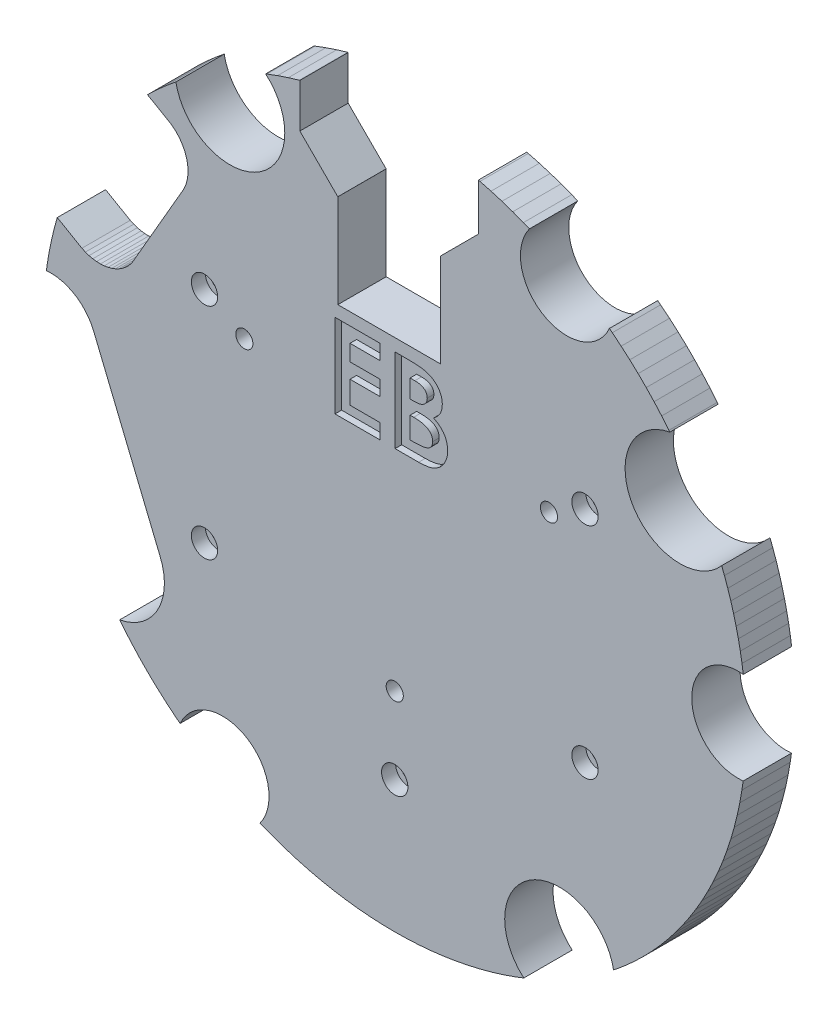
SolidWorks part; units mm, degrees
ref_plane "Płaszczyzna przednia" through (0, 0, 0) normal (0, 0, 1) x (1, 0, 0)
ref_plane "Płaszczyzna górna" through (0, 0, 0) normal (0, 1, 0) x (1, 0, 0)
ref_plane "Płaszczyzna prawa" through (0, 0, 0) normal (1, 0, 0) x (0, 0, -1)
sketch "mandaryna baza " plane through (0, 0, 0) normal (0, 0, 1) x (1, 0, 0)
  line L0 (16.9072, 3.25) -> (54.9039, 3.25)
  line L1 (30.2665, 45.9232) -> (11.2682, 13.017)
  line L2 (5.639, 16.267) -> (24.6374, 49.1732)
  line L3 (-24.6374, 49.1732) -> (-5.639, 16.267)
  line L4 (-11.2682, 13.017) -> (-30.2665, 45.9232)
  line L5 (-54.9039, 3.25) -> (-16.9072, 3.25)
  line L6 (4.5506, 66.6591) -> (4.5491, 66.657) construction
  line L7 (24.4667, 51.9252) -> (4.5506, 66.6591) construction
  line L8 (5.8555, 16.142) -> (24.861, 49.0605) construction
  line L9 (-24.861, 49.0605) -> (-5.8555, 16.142) construction
  line L10 (-4.5491, 66.657) -> (-4.5506, 66.6591) construction
  line L11 (30.0571, 46.0605) -> (11.0517, 13.142) construction
  line L12 (67.2135, 4.9608) -> (71.9198, 8.4424) construction
  line L13 (16.9072, 3) -> (54.9181, 3) construction
  line L14 (-16.9072, -3.25) -> (-54.9039, -3.25)
  line L15 (-30.2665, -45.9232) -> (-11.2682, -13.017)
  line L16 (54.9181, -3) -> (16.9072, -3) construction
  line L17 (71.9198, -8.4424) -> (67.2135, -4.9608) construction
  line L18 (11.0517, -13.142) -> (30.0571, -46.0605) construction
  line L19 (-5.639, -16.267) -> (-24.6374, -49.1732)
  line L20 (24.6374, -49.1732) -> (5.639, -16.267)
  line L21 (11.2682, -13.017) -> (30.2665, -45.9232)
  line L22 (54.9039, -3.25) -> (16.9072, -3.25)
  line L23 (4.5506, -66.6591) -> (24.4667, -51.9252) construction
  line L24 (4.5491, -66.657) -> (4.5506, -66.6591) construction
  line L25 (-4.5506, -66.6591) -> (-4.5491, -66.657) construction
  line L26 (-24.4667, -51.9252) -> (-4.5506, -66.6591) construction
  line L27 (-67.2135, -4.9608) -> (-71.9198, -8.4424) construction
  line L28 (-16.9072, -3) -> (-54.9181, -3) construction
  line L29 (-54.9181, 3) -> (-16.9072, 3) construction
  line L30 (-71.9198, 8.4424) -> (-67.2135, 4.9608) construction
  line L31 (-11.0517, 13.142) -> (-30.0571, 46.0605) construction
  line L37 (-13.1504, 53.4048) -> (-13.1504, 36.9511)
  line L38 (-13.1504, 36.9511) -> (10.6176, 36.9511)
  line L39 (10.6176, 36.9511) -> (10.6176, 53.9654)
  circle A0 centre (0, 0) radius 85 construction
  circle A1 centre (0, 0) radius 6 construction
  arc A2 (11.2682, 13.017) -> (16.9072, 3.25) centre (16.9072, 9.7614) ccw
  arc A3 (-5.639, 16.267) -> (5.639, 16.267) centre (0, 19.5227) ccw
  arc A4 (-16.9072, 3.25) -> (-11.2682, 13.017) centre (-16.9072, 9.7614) ccw
  arc A5 (25.0093, 49.3174) -> (24.4667, 51.9252) centre (23.2772, 50.3174) ccw construction
  arc A6 (-5.8555, 16.142) -> (5.8555, 16.142) centre (0, 19.5227) ccw construction
  arc A7 (-4.5491, 66.657) -> (-0.4915, 64.6309) centre (-0.5295, 69.6307) ccw construction
  arc A8 (0.4915, 64.6309) -> (-0.4915, 64.6309) centre (0, 0) ccw construction
  arc A9 (0.4915, 64.6309) -> (4.5491, 66.657) centre (0.5295, 69.6307) ccw construction
  arc A10 (51.1946, 58.8482) -> (35.971, 56.3035) centre (44.6312, 51.3035) ccw construction
  arc A11 (75.6742, 18.9054) -> (51.1946, 58.8482) centre (0, 0) ccw construction
  arc A12 (71.9198, 8.4424) -> (75.6742, 18.9054) centre (65.9724, 16.4816) ccw construction
  arc A13 (61.2662, 3) -> (67.2135, 4.9608) centre (61.2662, 13) ccw construction
  arc A14 (11.0517, 13.142) -> (16.9072, 3) centre (16.9072, 9.7614) ccw construction
  arc A15 (-11.2682, -13.017) -> (-16.9072, -3.25) centre (-16.9072, -9.7614) ccw
  arc A16 (67.2135, -4.9608) -> (61.2662, -3) centre (61.2662, -13) ccw construction
  arc A17 (75.6742, -18.9054) -> (71.9198, -8.4424) centre (65.9724, -16.4816) ccw construction
  arc A18 (14.9118, -76.5613) -> (56.0831, -54.2097) centre (0, 0) ccw construction
  arc A19 (3, -66.7458) -> (14.9118, -76.5613) centre (13, -66.7458) ccw construction
  arc A20 (16.9072, -3) -> (11.0517, -13.142) centre (16.9072, -9.7614) ccw construction
  arc A21 (5.639, -16.267) -> (-5.639, -16.267) centre (0, -19.5227) ccw
  arc A22 (4.5491, -66.657) -> (0.4915, -64.6309) centre (0.5295, -69.6307) ccw construction
  arc A23 (-0.4915, -64.6309) -> (0.4915, -64.6309) centre (0, 0) ccw construction
  arc A24 (-0.4915, -64.6309) -> (-4.5491, -66.657) centre (-0.5295, -69.6307) ccw construction
  arc A25 (-25.0093, -49.3174) -> (-24.4667, -51.9252) centre (-23.2772, -50.3174) ccw construction
  arc A26 (5.8555, -16.142) -> (-5.8555, -16.142) centre (0, -19.5227) ccw construction
  arc A27 (16.9072, -3.25) -> (11.2682, -13.017) centre (16.9072, -9.7614) ccw
  arc A28 (30.2665, -45.9232) -> (54.9039, -3.25) centre (0, 0) ccw
  arc A29 (24.6374, 49.1732) -> (10.6176, 53.9654) centre (0, 0) ccw
  arc A30 (-51.1946, -58.8482) -> (-35.971, -56.3035) centre (-44.6312, -51.3035) ccw construction
  arc A31 (-75.6742, -18.9054) -> (-51.1946, -58.8482) centre (0, 0) ccw construction
  arc A32 (-71.9198, -8.4424) -> (-75.6742, -18.9054) centre (-65.9724, -16.4816) ccw construction
  arc A33 (-61.2662, -3) -> (-67.2135, -4.9608) centre (-61.2662, -13) ccw construction
  arc A34 (-11.0517, -13.142) -> (-16.9072, -3) centre (-16.9072, -9.7614) ccw construction
  arc A35 (-30.2665, 45.9232) -> (-54.9039, 3.25) centre (0, 0) ccw
  arc A36 (-54.9039, -3.25) -> (-30.2665, -45.9232) centre (0, 0) ccw
  arc A37 (-24.6374, -49.1732) -> (24.6374, -49.1732) centre (0, 0) ccw
  arc A38 (54.9039, 3.25) -> (30.2665, 45.9232) centre (0, 0) ccw
  arc A39 (-67.2135, 4.9608) -> (-61.2662, 3) centre (-61.2662, 13) ccw construction
  arc A40 (-75.6742, 18.9054) -> (-71.9198, 8.4424) centre (-65.9724, 16.4816) ccw construction
  arc A41 (-51.1946, 58.8482) -> (-75.6742, 18.9054) centre (0, 0) ccw construction
  arc A42 (-35.971, 56.3035) -> (-51.1946, 58.8482) centre (-44.6312, 51.3035) ccw construction
  arc A43 (-16.9072, 3) -> (-11.0517, 13.142) centre (-16.9072, 9.7614) ccw construction
  arc A44 (-13.1504, 53.4048) -> (-24.6374, 49.1732) centre (0, 0) ccw
extrude "Dodanie-wyciągnięcie1" add sketch "mandaryna baza " along normal blind 5
sketch "MB_wyciecia" plane through (0, 0, 0) normal (0, 0, 1) x (1, 0, 0)
  line L0 (-0.1242, -22.5327) -> (-0.3125, 0) construction
  line L1 (-34.4185, 20.0049) -> (-0.3125, 0) construction
  line L2 (13.0498, 7.7147) -> (34.7962, 20.27) construction
  line L7 (-35.0924, 72.0577) -> (-32.5738, 67.4522)
  line L8 (-42.3633, 62.4733) -> (-44.721, 66.557)
  line L9 (19.0018, 77.646) -> (19.0018, 67.2099)
  line L10 (19.0018, 67.2099) -> (10.3758, 58.5839)
  line L11 (10.3758, 58.5839) -> (10.3758, 37.3074)
  line L12 (10.3758, 37.3074) -> (-12.9922, 37.3074)
  line L13 (-12.9922, 37.3074) -> (-12.9922, 58.5739)
  line L14 (-12.9922, 58.5739) -> (-21.6382, 67.2099)
  line L15 (-21.6382, 67.2099) -> (-21.7619, 77.0835)
  line L19 (42.2923, -62.1866) -> (44.5033, -66.2834)
  line L20 (-58.3058, 54.9924) -> (-50.9165, 49.4506)
  line L21 (-70.2019, 38.6255) -> (-62.5311, 33.1574)
  line L23 (-74.5615, -9.724) -> (-68.7602, -8.3848)
  line L24 (-76.1011, -24.6775) -> (-65.5639, -22.245)
  line L25 (67.774, 32.961) -> (71.6123, 35.0537)
  line L26 (62.1773, 42.4277) -> (65.9654, 44.8239)
  line L28 (32.3345, -66.7767) -> (34.11, -72.1952)
  line L29 (-62.2802, -42.12) -> (-66.1005, -44.9806)
  line L30 (-67.4562, -32.4335) -> (-72.2043, -34.4007)
  line L31 (-58.3058, 54.9924) -> (-58.3719, 55.055)
  line L32 (-70.2019, 38.6255) -> (-70.3266, 38.7295)
  line L34 (-76.1011, -24.6775) -> (-76.3992, -24.7542)
  line L35 (-72.2043, -34.4007) -> (-72.5196, -34.4687)
  line L36 (-66.1005, -44.9806) -> (-66.3559, -45.1687)
  line L37 (34.11, -72.1952) -> (34.1253, -72.2217)
  arc A1 (-42.3633, 62.4733) -> (-32.5738, 67.4522) centre (-37.5482, 65.1194) ccw
  arc A3 (-62.5311, 33.1574) -> (-50.9165, 49.4506) centre (-56.5654, 41.1911) ccw
  arc A4 (-65.5639, -22.245) -> (-68.7602, -8.3848) centre (-67.0693, -15.2935) ccw
  arc A5 (-62.2802, -42.12) -> (-67.4562, -32.4335) centre (-64.9966, -37.3454) ccw
  arc A7 (62.1773, 42.4277) -> (67.774, 32.961) centre (64.9255, 37.6647) ccw
  arc A8 (42.2923, -62.1866) -> (32.3345, -66.7767) centre (37.4627, -64.8056) ccw
  arc A9 (-21.7619, 77.0835) -> (-35.0924, 72.0577) centre (-0.3125, 0) ccw
  arc A10 (-44.721, 66.557) -> (-58.3719, 55.055) centre (-0.3125, 0) ccw
  arc A11 (-70.3266, 38.7295) -> (-79.6124, 10.6528) centre (-0.3125, 0) ccw
  arc A12 (-76.3992, -24.7542) -> (-72.5196, -34.4687) centre (-0.3125, 0) ccw
  arc A13 (-66.3559, -45.1687) -> (-48.9339, -63.5445) centre (-0.3125, 0) ccw
  arc A14 (44.5033, -66.2834) -> (78.9866, -10.6577) centre (-0.3125, 0) ccw
  arc A15 (65.9654, 44.8239) -> (48.7749, 63.1852) centre (-0.3125, 0) ccw
  arc A16 (79.0174, 10.4265) -> (78.9866, -10.6577) centre (78.1738, -0.1144) ccw
  arc A18 (-30.7368, -74.0021) -> (-48.9339, -63.5445) centre (-39.186, -67.6433) ccw
  arc A21 (30.5908, 73.8033) -> (48.7749, 63.1852) centre (39.186, 67.6433) ccw
  circle A22 centre (38.9878, -67.7577) radius 10.5746
  circle A23 centre (-38.9878, 67.7577) radius 10.5746
  arc A24 (30.5908, 73.8033) -> (19.0018, 77.646) centre (-0.3125, 0) ccw
  arc A25 (79.0174, 10.4265) -> (71.6123, 35.0537) centre (-0.3125, 0) ccw
  arc A26 (-30.7368, -74.0021) -> (34.1253, -72.2217) centre (-0.3125, 0) ccw
  arc A28 (-74.5615, -9.724) -> (-79.6124, 10.6528) centre (-78.3301, 0.1563) ccw
  arc A29 (-84.5664, -8.3092) -> (-82.6226, -9.4789) centre (-78.1738, 0.1144) ccw
  point P46 (0, 0)
  dimension "D6" = 10.9879
  dimension "D7" = 10.9884
  dimension "D8" = 20.013
  dimension "D9" = 14.2253
  dimension "D10" = 10.9979
  dimension "D11" = 160.0243
  dimension "D3" = 80.0122
  dimension "D2" = 39.54
  dimension "D4" = 6
  dimension "D13" = 40.54
  dimension "D15" = 39.54
sketch "EB_" plane through (0, 0, 0) normal (0, 0, 1) x (1, 0, 0)
  line L0 (0, 0) -> (-22.7294, 43.3106) construction
  line L1 (0, 0) -> (25.5306, 43.3106) construction
  line L2 (0, 0) -> (-19.5544, -22.7294)
  line L3 (0, 0) -> (22.3556, -22.7294)
  line L4 (-71.5796, -7.9834) -> (-71.3126, -9.14)
  line L5 (-71.3126, -9.14) -> (-68.5352, -8.4988)
  line L660 (-59.4357, 22.62) -> (-59.654, 22.2418)
  line L661 (-59.654, 22.2418) -> (-60.1628, 21.5318)
  line L662 (-60.1628, 21.5318) -> (-60.7387, 20.8751)
  line L663 (-60.7387, 20.8751) -> (-61.3762, 20.278)
  line L664 (-61.3762, 20.278) -> (-62.0692, 19.7462)
  line L665 (-62.0692, 19.7462) -> (-62.811, 19.285)
  line L666 (-62.811, 19.285) -> (-63.5944, 18.8986)
  line L667 (-63.5944, 18.8986) -> (-64.4119, 18.591)
  line L668 (-64.4119, 18.591) -> (-65.2556, 18.3649)
  line L669 (-65.2556, 18.3649) -> (-66.1174, 18.2226)
  line L670 (-66.1174, 18.2226) -> (-66.989, 18.1655)
  line L671 (-66.989, 18.1655) -> (-67.862, 18.1941)
  line L672 (-67.862, 18.1941) -> (-68.728, 18.3081)
  line L673 (-68.728, 18.3081) -> (-69.5787, 18.5064)
  line L674 (-69.5787, 18.5064) -> (-70.4058, 18.7872)
  line L675 (-70.4058, 18.7872) -> (-71.2014, 19.1477)
  line L676 (-71.2014, 19.1477) -> (-71.5796, 19.366)
  line L677 (-71.5796, 19.366) -> (-76.8174, 22.3901)
  line L678 (-76.8174, 22.3901) -> (-76.8834, 22.1744)
  line L679 (-76.8834, 22.1744) -> (-77.5625, 19.6678)
  line L680 (-77.5625, 19.6678) -> (-78.1599, 17.1405)
  line L681 (-78.1599, 17.1405) -> (-78.6749, 14.5952)
  line L682 (-78.6749, 14.5952) -> (-79.1071, 12.0345)
  line L683 (-79.1071, 12.0345) -> (-79.2897, 10.6872)
  line L693 (-68.5352, -8.4988) -> (-68.1939, -8.42)
  line L694 (-68.1939, -8.42) -> (-67.4966, -8.3528)
  line L695 (-67.4966, -8.3528) -> (-66.7965, -8.3773)
  line L696 (-66.7965, -8.3773) -> (-66.1056, -8.4929)
  line L697 (-66.1056, -8.4929) -> (-65.4357, -8.6977)
  line L698 (-65.4357, -8.6977) -> (-64.7982, -8.9882)
  line L699 (-64.7982, -8.9882) -> (-64.2042, -9.3594)
  line L700 (-64.2042, -9.3594) -> (-63.6636, -9.805)
  line L701 (-63.6636, -9.805) -> (-63.1859, -10.3174)
  line L702 (-63.1859, -10.3174) -> (-62.7791, -10.8877)
  line L703 (-62.7791, -10.8877) -> (-62.4502, -11.5062)
  line L704 (-62.4502, -11.5062) -> (-62.2049, -12.1624)
  line L705 (-62.2049, -12.1624) -> (-62.1261, -12.5037)
  line L706 (-62.1261, -12.5037) -> (-61.3306, -15.949)
  line L707 (-61.3306, -15.949) -> (-61.2518, -16.2903)
  line L708 (-61.2518, -16.2903) -> (-61.1847, -16.9876)
  line L709 (-61.1847, -16.9876) -> (-61.2092, -17.6877)
  line L710 (-61.2092, -17.6877) -> (-61.3248, -18.3787)
  line L711 (-61.3248, -18.3787) -> (-61.5296, -19.0486)
  line L712 (-61.5296, -19.0486) -> (-61.8201, -19.686)
  line L713 (-61.8201, -19.686) -> (-62.1913, -20.2801)
  line L714 (-62.1913, -20.2801) -> (-62.6369, -20.8206)
  line L715 (-62.6369, -20.8206) -> (-63.1492, -21.2984)
  line L716 (-63.1492, -21.2984) -> (-63.7196, -21.7052)
  line L717 (-63.7196, -21.7052) -> (-64.3381, -22.0341)
  line L718 (-64.3381, -22.0341) -> (-64.9942, -22.2794)
  line L719 (-64.9942, -22.2794) -> (-65.3355, -22.3582)
  line L720 (-65.3355, -22.3582) -> (-76.0559, -24.8332)
  line L721 (-76.0559, -24.8332) -> (-75.5463, -26.3728)
  line L722 (-75.5463, -26.3728) -> (-74.6507, -28.8104)
  line L723 (-74.6507, -28.8104) -> (-74.4178, -29.3858)
  line L756 (-62.6093, -49.8114) -> (-61.8317, -50.7929)
  line L757 (-61.8317, -50.7929) -> (-60, -52.944)
  line L758 (-60, -52.944) -> (-58.0936, -55.0292)
  line L759 (-58.0936, -55.0292) -> (-56.1147, -57.0457)
  line L760 (-56.1147, -57.0457) -> (-54.0659, -58.9911)
  line L761 (-54.0659, -58.9911) -> (-51.9496, -60.863)
  line L762 (-51.9496, -60.863) -> (-49.7687, -62.659)
  line L763 (-49.7687, -62.659) -> (-48.854, -63.3595)
  line L770 (-30.6643, -73.9045) -> (-30.3309, -74.048)
  line L771 (-30.3309, -74.048) -> (-27.6979, -75.0726)
  line L772 (-27.6979, -75.0726) -> (-25.0304, -76.0036)
  line L773 (-25.0304, -76.0036) -> (-22.3317, -76.8399)
  line L774 (-22.3317, -76.8399) -> (-19.6051, -77.5804)
  line L775 (-19.6051, -77.5804) -> (-16.8541, -78.2241)
  line L776 (-16.8541, -78.2241) -> (-14.0821, -78.7703)
  line L777 (-14.0821, -78.7703) -> (-11.2926, -79.2184)
  line L778 (-11.2926, -79.2184) -> (-8.4889, -79.5676)
  line L779 (-8.4889, -79.5676) -> (-5.6747, -79.8177)
  line L780 (-5.6747, -79.8177) -> (-2.8534, -79.9683)
  line L781 (-2.8534, -79.9683) -> (-0.0286, -80.0192)
  line L782 (-0.0286, -80.0192) -> (2.7963, -79.9703)
  line L783 (2.7963, -79.9703) -> (5.6177, -79.8218)
  line L784 (5.6177, -79.8218) -> (8.4321, -79.5737)
  line L785 (8.4321, -79.5737) -> (11.236, -79.2264)
  line L786 (11.236, -79.2264) -> (14.0259, -78.7804)
  line L787 (14.0259, -78.7804) -> (16.7983, -78.2361)
  line L788 (16.7983, -78.2361) -> (19.5497, -77.5943)
  line L789 (19.5497, -77.5943) -> (22.2768, -76.8558)
  line L790 (22.2768, -76.8558) -> (24.9761, -76.0215)
  line L791 (24.9761, -76.0215) -> (27.6443, -75.0924)
  line L792 (27.6443, -75.0924) -> (29.3845, -74.4166)
  line L825 (49.8125, -62.6148) -> (50.2037, -62.3107)
  line L826 (50.2037, -62.3107) -> (52.3536, -60.5156)
  line L827 (52.3536, -60.5156) -> (54.4394, -58.6463)
  line L828 (54.4394, -58.6463) -> (56.4584, -56.7052)
  line L829 (56.4584, -56.7052) -> (58.4083, -54.6947)
  line L830 (58.4083, -54.6947) -> (60.2867, -52.6171)
  line L831 (60.2867, -52.6171) -> (62.0911, -50.475)
  line L832 (62.0911, -50.475) -> (63.8195, -48.2711)
  line L833 (63.8195, -48.2711) -> (65.4698, -46.0081)
  line L834 (65.4698, -46.0081) -> (67.0398, -43.6887)
  line L835 (67.0398, -43.6887) -> (68.5277, -41.3158)
  line L836 (68.5277, -41.3158) -> (69.9316, -38.8923)
  line L837 (69.9316, -38.8923) -> (71.2498, -36.4211)
  line L838 (71.2498, -36.4211) -> (72.4808, -33.9053)
  line L839 (72.4808, -33.9053) -> (73.623, -31.348)
  line L840 (73.623, -31.348) -> (74.6749, -28.7523)
  line L841 (74.6749, -28.7523) -> (75.6354, -26.1213)
  line L842 (75.6354, -26.1213) -> (76.5032, -23.4583)
  line L843 (76.5032, -23.4583) -> (77.2773, -20.7666)
  line L844 (77.2773, -20.7666) -> (77.9567, -18.0495)
  line L845 (77.9567, -18.0495) -> (78.5407, -15.3102)
  line L846 (78.5407, -15.3102) -> (79.0284, -12.5522)
  line L847 (79.0284, -12.5522) -> (79.2994, -10.6289)
  line L856 (79.3336, 10.3964) -> (79.0449, 12.4201)
  line L857 (79.0449, 12.4201) -> (78.6613, 14.6547)
  line L858 (78.6613, 14.6547) -> (78.2145, 16.8775)
  line L859 (78.2145, 16.8775) -> (77.7049, 19.0868)
  line L860 (77.7049, 19.0868) -> (77.1329, 21.2808)
  line L861 (77.1329, 21.2808) -> (76.499, 23.4576)
  line L862 (76.499, 23.4576) -> (75.8037, 25.6157)
  line L863 (75.8037, 25.6157) -> (75.0475, 27.7531)
  line L864 (75.0475, 27.7531) -> (74.4174, 29.3854)
  line L897 (62.6156, 49.8127) -> (62.4143, 50.0722)
  line L898 (62.4143, 50.0722) -> (60.7549, 52.0732)
  line L899 (60.7549, 52.0732) -> (59.0313, 54.0192)
  line L900 (59.0313, 54.0192) -> (57.2455, 55.9082)
  line L901 (57.2455, 55.9082) -> (55.3992, 57.7382)
  line L902 (55.3992, 57.7382) -> (53.4945, 59.5072)
  line L903 (53.4945, 59.5072) -> (51.5333, 61.2135)
  line L904 (51.5333, 61.2135) -> (49.5177, 62.8551)
  line L905 (49.5177, 62.8551) -> (48.8544, 63.3604)
  line L913 (30.6602, 73.899) -> (29.2981, 74.4606)
  line L914 (29.2981, 74.4606) -> (26.864, 75.373)
  line L915 (26.864, 75.373) -> (24.4015, 76.2059)
  line L916 (24.4015, 76.2059) -> (21.9132, 76.9583)
  line L917 (21.9132, 76.9583) -> (19.4018, 77.6295)
  line L918 (19.4018, 77.6295) -> (19.0436, 77.7128)
  line L919 (19.0436, 77.7128) -> (19.0437, 67.0537)
  line L920 (19.0437, 67.0537) -> (10.4176, 58.4277)
  line L921 (10.4176, 58.4277) -> (10.4176, 37.1511)
  line L922 (10.4176, 37.1511) -> (-12.9504, 37.1511)
  line L923 (-12.9504, 37.1511) -> (-12.9504, 58.4177)
  line L924 (-12.9504, 58.4177) -> (-12.9604, 58.4177)
  line L925 (-12.9604, 58.4177) -> (-21.5964, 67.0537)
  line L926 (-21.5964, 67.0537) -> (-21.5964, 77.0457)
  line L927 (-21.5964, 77.0457) -> (-21.7211, 77.0127)
  line L928 (-21.7211, 77.0127) -> (-24.2112, 76.2665)
  line L929 (-24.2112, 76.2665) -> (-26.6758, 75.4398)
  line L930 (-26.6758, 75.4398) -> (-29.1122, 74.5335)
  line L931 (-29.1122, 74.5335) -> (-29.3887, 74.4203)
  line L964 (-49.8133, 62.6189) -> (-49.8986, 62.5531)
  line L965 (-49.8986, 62.5531) -> (-51.9022, 60.9009)
  line L966 (-51.9022, 60.9009) -> (-53.8511, 59.1846)
  line L967 (-53.8511, 59.1846) -> (-55.7433, 57.406)
  line L968 (-55.7433, 57.406) -> (-56.2765, 56.8712)
  line L969 (-56.2765, 56.8712) -> (-51.5136, 54.1214)
  line L970 (-51.5136, 54.1214) -> (-51.1354, 53.903)
  line L971 (-51.1354, 53.903) -> (-50.4254, 53.3942)
  line L972 (-50.4254, 53.3942) -> (-49.7687, 52.8183)
  line L973 (-49.7687, 52.8183) -> (-49.1716, 52.1808)
  line L974 (-49.1716, 52.1808) -> (-48.6398, 51.4878)
  line L975 (-48.6398, 51.4878) -> (-48.1786, 50.746)
  line L976 (-48.1786, 50.746) -> (-47.7923, 49.9626)
  line L977 (-47.7923, 49.9626) -> (-47.4846, 49.1452)
  line L978 (-47.4846, 49.1452) -> (-47.2585, 48.3014)
  line L979 (-47.2585, 48.3014) -> (-47.1162, 47.4396)
  line L980 (-47.1162, 47.4396) -> (-47.0591, 46.568)
  line L981 (-47.0591, 46.568) -> (-47.0877, 45.695)
  line L982 (-47.0877, 45.695) -> (-47.2017, 44.829)
  line L983 (-47.2017, 44.829) -> (-47.4, 43.9784)
  line L984 (-47.4, 43.9784) -> (-47.6808, 43.1512)
  line L985 (-47.6808, 43.1512) -> (-48.0413, 42.3556)
  line L986 (-48.0413, 42.3556) -> (-48.2597, 41.9774)
  line L987 (-48.2597, 41.9774) -> (-59.4357, 22.62)
  arc A0 (64.3736, 47.5139) -> (73.3082, 32.0629) centre (64.9348, 37.5297) ccw construction
  circle A3 centre (0, -32.54) radius 1.6
  circle A4 centre (35.1087, 20.27) radius 1.6
  circle A5 centre (-34.2427, 19.77) radius 1.6
  arc A7 (59.3647, 45.8348) -> (-28.5574, 69.3504) centre (0, 0) ccw construction
  arc A9 (-45.8348, 59.3647) -> (-69.3504, -28.5574) centre (0, 0) ccw construction
  arc A10 (-67.5212, -32.6479) -> (69.3504, 28.5574) centre (0, 0) ccw construction
  arc A12 (-30.6643, -73.9045) -> (-48.854, -63.3595) centre (-39.186, -67.6433) ccw
  arc A13 (79.3336, 10.3964) -> (79.2994, -10.6289) centre (78.1738, -0.1144) ccw
  arc A14 (30.6602, 73.899) -> (48.8544, 63.3604) centre (39.186, 67.6433) ccw
  arc A15 (-71.5796, -7.9834) -> (-79.2897, 10.6872) centre (-78.3301, 0.1563) ccw
  arc A16 (62.6156, 49.8127) -> (74.4174, 29.3854) centre (64.9348, 37.5297) ccw
  arc A17 (49.8125, -62.6148) -> (29.3845, -74.4166) centre (37.5297, -64.9348) ccw
  arc A18 (-62.6093, -49.8114) -> (-74.4178, -29.3858) centre (-64.9348, -37.5297) ccw
  arc A19 (-49.8133, 62.6189) -> (-29.3887, 74.4203) centre (-37.5297, 64.9348) ccw
  point P38 (0, 0)
  point P80 (0, 0)
  dimension "D5" = 150
  dimension "D6" = 20
  dimension "D8" = 25
  dimension "D1" = 29.9833
  dimension "D2" = 31.881
  dimension "D3" = 50.2755
  dimension "D4" = 48.9125
  dimension "D9" = 4
extrude "Dodanie-wyciągnięcie2" add sketch "EB_" along direction (0, 0, 1) on the side of the normal blind 11 from offset 5
sketch "Sketch2" plane through (0, 0, 16) normal (0, 0, 1) x (1, 0, 0)
  line L0 (-1.2664, 37.1511) -> (-1.2664, -19.909) construction
  line L2 (-18.1388, 15.2871) -> (15.6061, 15.2871) construction
  line L3 (10.4176, 37.1511) -> (-12.9504, 37.1511) construction
  text T0 "EB" font "Century Gothic" height in points 72
  point P7 (-1.2664, 15.2871)
extrude "Cut-Extrude2" cut sketch "Sketch2" against normal blind 1.5
sketch "Sketch4" plane through (0, 0, 16) normal (0, 0, 1) x (1, 0, 0)
  line L0 (-68.5482, 4.1734) -> (-53.3719, -32.7811)
  line L172 (-49.8133, 62.6189) -> (-49.8986, 62.5531)
  line L173 (-49.8986, 62.5531) -> (-51.9022, 60.9009)
  line L174 (-51.9022, 60.9009) -> (-53.8511, 59.1846)
  line L175 (-53.8511, 59.1846) -> (-55.7433, 57.406)
  line L176 (-55.7433, 57.406) -> (-56.2765, 56.8712)
  line L177 (-56.2765, 56.8712) -> (-51.5136, 54.1214)
  line L178 (-51.5136, 54.1214) -> (-51.1354, 53.903)
  line L179 (-51.1354, 53.903) -> (-50.4254, 53.3942)
  line L180 (-50.4254, 53.3942) -> (-49.7687, 52.8183)
  line L181 (-49.7687, 52.8183) -> (-49.1716, 52.1808)
  line L182 (-49.1716, 52.1808) -> (-48.6398, 51.4878)
  line L183 (-48.6398, 51.4878) -> (-48.1786, 50.746)
  line L184 (-48.1786, 50.746) -> (-47.7923, 49.9626)
  line L185 (-47.7923, 49.9626) -> (-47.4846, 49.1452)
  line L186 (-47.4846, 49.1452) -> (-47.2585, 48.3014)
  line L187 (-47.2585, 48.3014) -> (-47.1162, 47.4396)
  line L188 (-47.1162, 47.4396) -> (-47.0591, 46.568)
  line L189 (-47.0591, 46.568) -> (-47.0877, 45.695)
  line L190 (-47.0877, 45.695) -> (-47.2017, 44.829)
  line L191 (-47.2017, 44.829) -> (-47.4, 43.9784)
  line L192 (-47.4, 43.9784) -> (-47.6808, 43.1512)
  line L193 (-47.6808, 43.1512) -> (-48.0413, 42.3556)
  line L194 (-48.0413, 42.3556) -> (-48.2597, 41.9774)
  line L195 (-48.2597, 41.9774) -> (-59.4357, 22.62)
  line L196 (-59.4357, 22.62) -> (-59.654, 22.2418)
  line L197 (-59.654, 22.2418) -> (-60.1628, 21.5318)
  line L198 (-60.1628, 21.5318) -> (-60.7387, 20.8751)
  line L199 (-60.7387, 20.8751) -> (-61.3762, 20.278)
  line L200 (-61.3762, 20.278) -> (-62.0692, 19.7462)
  line L201 (-62.0692, 19.7462) -> (-62.811, 19.285)
  line L202 (-62.811, 19.285) -> (-63.5944, 18.8986)
  line L203 (-63.5944, 18.8986) -> (-64.4119, 18.591)
  line L204 (-64.4119, 18.591) -> (-65.2556, 18.3649)
  line L205 (-65.2556, 18.3649) -> (-66.1174, 18.2226)
  line L206 (-66.1174, 18.2226) -> (-66.989, 18.1655)
  line L207 (-66.989, 18.1655) -> (-67.862, 18.1941)
  line L208 (-67.862, 18.1941) -> (-68.728, 18.3081)
  line L209 (-68.728, 18.3081) -> (-69.5787, 18.5064)
  line L210 (-69.5787, 18.5064) -> (-70.4058, 18.7872)
  line L211 (-70.4058, 18.7872) -> (-71.2014, 19.1477)
  line L212 (-71.2014, 19.1477) -> (-71.5796, 19.366)
  line L213 (-71.5796, 19.366) -> (-76.8174, 22.3901)
  line L214 (-76.8174, 22.3901) -> (-76.8834, 22.1744)
  line L215 (-76.8834, 22.1744) -> (-77.5625, 19.6678)
  line L216 (-77.5625, 19.6678) -> (-78.1599, 17.1405)
  line L217 (-78.1599, 17.1405) -> (-78.6749, 14.5952)
  line L218 (-78.6749, 14.5952) -> (-79.1071, 12.0345)
  line L219 (-79.1071, 12.0345) -> (-79.2897, 10.6872)
  line L220 (-71.5796, -7.9834) -> (-71.3126, -9.14)
  line L221 (-71.3126, -9.14) -> (-68.5352, -8.4988)
  line L222 (-68.5352, -8.4988) -> (-68.1939, -8.42)
  line L223 (-68.1939, -8.42) -> (-67.4966, -8.3528)
  line L224 (-67.4966, -8.3528) -> (-66.7965, -8.3773)
  line L225 (-66.7965, -8.3773) -> (-66.1056, -8.4929)
  line L226 (-66.1056, -8.4929) -> (-65.4357, -8.6977)
  line L227 (-65.4357, -8.6977) -> (-64.7982, -8.9882)
  line L228 (-64.7982, -8.9882) -> (-64.2042, -9.3594)
  line L229 (-64.2042, -9.3594) -> (-63.6636, -9.805)
  line L230 (-63.6636, -9.805) -> (-63.1859, -10.3174)
  line L231 (-63.1859, -10.3174) -> (-62.7791, -10.8877)
  line L232 (-62.7791, -10.8877) -> (-62.4502, -11.5062)
  line L233 (-62.4502, -11.5062) -> (-62.2049, -12.1624)
  line L234 (-62.2049, -12.1624) -> (-62.1261, -12.5037)
  line L235 (-62.1261, -12.5037) -> (-61.3306, -15.949)
  line L236 (-61.3306, -15.949) -> (-61.2518, -16.2903)
  line L237 (-61.2518, -16.2903) -> (-61.1847, -16.9876)
  line L238 (-61.1847, -16.9876) -> (-61.2092, -17.6877)
  line L239 (-61.2092, -17.6877) -> (-61.3248, -18.3787)
  line L240 (-61.3248, -18.3787) -> (-61.5296, -19.0486)
  line L241 (-61.5296, -19.0486) -> (-61.8201, -19.686)
  line L242 (-61.8201, -19.686) -> (-62.1913, -20.2801)
  line L243 (-62.1913, -20.2801) -> (-62.6369, -20.8206)
  line L244 (-62.6369, -20.8206) -> (-63.1492, -21.2984)
  line L245 (-63.1492, -21.2984) -> (-63.7196, -21.7052)
  line L246 (-63.7196, -21.7052) -> (-64.3381, -22.0341)
  line L247 (-64.3381, -22.0341) -> (-64.9942, -22.2794)
  line L248 (-64.9942, -22.2794) -> (-65.3355, -22.3582)
  line L249 (-65.3355, -22.3582) -> (-76.0559, -24.8332)
  line L250 (-76.0559, -24.8332) -> (-75.5463, -26.3728)
  line L251 (-75.5463, -26.3728) -> (-74.6507, -28.8104)
  line L252 (-74.6507, -28.8104) -> (-74.4178, -29.3858)
  line L253 (-62.6093, -49.8114) -> (-61.8317, -50.7929)
  line L254 (-61.8317, -50.7929) -> (-60, -52.944)
  line L255 (-60, -52.944) -> (-58.0936, -55.0292)
  line L256 (-58.0936, -55.0292) -> (-56.1147, -57.0457)
  line L257 (-56.1147, -57.0457) -> (-54.0659, -58.9911)
  line L258 (-54.0659, -58.9911) -> (-51.9496, -60.863)
  line L259 (-51.9496, -60.863) -> (-49.7687, -62.659)
  line L260 (-49.7687, -62.659) -> (-48.854, -63.3595)
  line L261 (-30.6643, -73.9045) -> (-30.3309, -74.048)
  line L262 (-30.3309, -74.048) -> (-27.6979, -75.0726)
  line L263 (-27.6979, -75.0726) -> (-25.0304, -76.0036)
  line L264 (-25.0304, -76.0036) -> (-22.3317, -76.8399)
  line L265 (-22.3317, -76.8399) -> (-19.6051, -77.5804)
  line L266 (-19.6051, -77.5804) -> (-16.8541, -78.2241)
  line L267 (-16.8541, -78.2241) -> (-14.0821, -78.7703)
  line L268 (-14.0821, -78.7703) -> (-11.2926, -79.2184)
  line L269 (-11.2926, -79.2184) -> (-8.4889, -79.5676)
  line L270 (-8.4889, -79.5676) -> (-5.6747, -79.8177)
  line L271 (-5.6747, -79.8177) -> (-2.8534, -79.9683)
  line L272 (-2.8534, -79.9683) -> (-0.0286, -80.0192)
  line L273 (-0.0286, -80.0192) -> (2.7963, -79.9703)
  line L274 (2.7963, -79.9703) -> (5.6177, -79.8218)
  line L275 (5.6177, -79.8218) -> (8.4321, -79.5737)
  line L276 (8.4321, -79.5737) -> (11.236, -79.2264)
  line L277 (11.236, -79.2264) -> (14.0259, -78.7804)
  line L278 (14.0259, -78.7804) -> (16.7983, -78.2361)
  line L279 (16.7983, -78.2361) -> (19.5497, -77.5943)
  line L280 (19.5497, -77.5943) -> (22.2768, -76.8558)
  line L281 (22.2768, -76.8558) -> (24.9761, -76.0215)
  line L282 (24.9761, -76.0215) -> (27.6443, -75.0924)
  line L283 (27.6443, -75.0924) -> (29.3845, -74.4166)
  line L284 (49.8125, -62.6148) -> (50.2037, -62.3107)
  line L285 (50.2037, -62.3107) -> (52.3536, -60.5156)
  line L286 (52.3536, -60.5156) -> (54.4394, -58.6463)
  line L287 (54.4394, -58.6463) -> (56.4584, -56.7052)
  line L288 (56.4584, -56.7052) -> (58.4083, -54.6947)
  line L289 (58.4083, -54.6947) -> (60.2867, -52.6171)
  line L290 (60.2867, -52.6171) -> (62.0911, -50.475)
  line L291 (62.0911, -50.475) -> (63.8195, -48.2711)
  line L292 (63.8195, -48.2711) -> (65.4698, -46.0081)
  line L293 (65.4698, -46.0081) -> (67.0398, -43.6887)
  line L294 (67.0398, -43.6887) -> (68.5277, -41.3158)
  line L295 (68.5277, -41.3158) -> (69.9316, -38.8923)
  line L296 (69.9316, -38.8923) -> (71.2498, -36.4211)
  line L297 (71.2498, -36.4211) -> (72.4808, -33.9053)
  line L298 (72.4808, -33.9053) -> (73.623, -31.348)
  line L299 (73.623, -31.348) -> (74.6749, -28.7523)
  line L300 (74.6749, -28.7523) -> (75.6354, -26.1213)
  line L301 (75.6354, -26.1213) -> (76.5032, -23.4583)
  line L302 (76.5032, -23.4583) -> (77.2773, -20.7666)
  line L303 (77.2773, -20.7666) -> (77.9567, -18.0495)
  line L304 (77.9567, -18.0495) -> (78.5407, -15.3102)
  line L305 (78.5407, -15.3102) -> (79.0284, -12.5522)
  line L306 (79.0284, -12.5522) -> (79.2994, -10.6289)
  line L307 (79.3336, 10.3964) -> (79.0449, 12.4201)
  line L308 (79.0449, 12.4201) -> (78.6613, 14.6547)
  line L309 (78.6613, 14.6547) -> (78.2145, 16.8775)
  line L310 (78.2145, 16.8775) -> (77.7049, 19.0868)
  line L311 (77.7049, 19.0868) -> (77.1329, 21.2808)
  line L312 (77.1329, 21.2808) -> (76.499, 23.4576)
  line L313 (76.499, 23.4576) -> (75.8037, 25.6157)
  line L314 (75.8037, 25.6157) -> (75.0475, 27.7531)
  line L315 (75.0475, 27.7531) -> (74.4174, 29.3854)
  line L316 (62.6156, 49.8127) -> (62.4143, 50.0722)
  line L317 (62.4143, 50.0722) -> (60.7549, 52.0732)
  line L318 (60.7549, 52.0732) -> (59.0313, 54.0192)
  line L319 (59.0313, 54.0192) -> (57.2455, 55.9082)
  line L320 (57.2455, 55.9082) -> (55.3992, 57.7382)
  line L321 (55.3992, 57.7382) -> (53.4945, 59.5072)
  line L322 (53.4945, 59.5072) -> (51.5333, 61.2135)
  line L323 (51.5333, 61.2135) -> (49.5177, 62.8551)
  line L324 (49.5177, 62.8551) -> (48.8544, 63.3604)
  line L325 (30.6602, 73.899) -> (29.2981, 74.4606)
  line L326 (29.2981, 74.4606) -> (26.864, 75.373)
  line L327 (26.864, 75.373) -> (24.4015, 76.2059)
  line L328 (24.4015, 76.2059) -> (21.9132, 76.9583)
  line L329 (21.9132, 76.9583) -> (19.4018, 77.6295)
  line L330 (19.4018, 77.6295) -> (19.0436, 77.7128)
  line L331 (19.0436, 77.7128) -> (19.0437, 67.0537)
  line L332 (19.0437, 67.0537) -> (10.4176, 58.4277)
  line L333 (10.4176, 58.4277) -> (10.4176, 37.1511)
  line L334 (10.4176, 37.1511) -> (-12.9504, 37.1511)
  line L335 (-12.9504, 37.1511) -> (-12.9504, 58.4177)
  line L336 (-12.9504, 58.4177) -> (-12.9604, 58.4177)
  line L337 (-12.9604, 58.4177) -> (-21.5964, 67.0537)
  line L338 (-21.5964, 67.0537) -> (-21.5964, 77.0457)
  line L339 (-21.5964, 77.0457) -> (-21.7211, 77.0127)
  line L340 (-21.7211, 77.0127) -> (-24.2112, 76.2665)
  line L341 (-24.2112, 76.2665) -> (-26.6758, 75.4398)
  line L342 (-26.6758, 75.4398) -> (-29.1122, 74.5335)
  line L343 (-29.1122, 74.5335) -> (-29.3887, 74.4203)
  line L392 (-71.5796, -7.9834) -> (-71.3126, -9.14)
  line L393 (-71.3126, -9.14) -> (-68.5352, -8.4988)
  line L394 (-68.5352, -8.4988) -> (-68.1939, -8.42)
  line L395 (-68.1939, -8.42) -> (-67.4966, -8.3528)
  line L396 (-67.4966, -8.3528) -> (-66.7965, -8.3773)
  line L397 (-66.7965, -8.3773) -> (-66.1056, -8.4929)
  line L398 (-66.1056, -8.4929) -> (-65.4357, -8.6977)
  line L399 (-65.4357, -8.6977) -> (-64.7982, -8.9882)
  line L400 (-64.7982, -8.9882) -> (-64.2042, -9.3594)
  line L401 (-64.2042, -9.3594) -> (-63.6636, -9.805)
  line L402 (-63.6636, -9.805) -> (-63.1859, -10.3174)
  line L403 (-63.1859, -10.3174) -> (-62.7791, -10.8877)
  line L404 (-62.7791, -10.8877) -> (-62.4502, -11.5062)
  line L405 (-62.4502, -11.5062) -> (-62.2049, -12.1624)
  line L406 (-62.2049, -12.1624) -> (-62.1261, -12.5037)
  line L407 (-62.1261, -12.5037) -> (-61.3306, -15.949)
  line L408 (-61.3306, -15.949) -> (-61.2518, -16.2903)
  line L409 (-61.2518, -16.2903) -> (-61.1847, -16.9876)
  line L410 (-61.1847, -16.9876) -> (-61.2092, -17.6877)
  line L411 (-61.2092, -17.6877) -> (-61.3248, -18.3787)
  line L412 (-61.3248, -18.3787) -> (-61.5296, -19.0486)
  line L413 (-61.5296, -19.0486) -> (-61.8201, -19.686)
  line L414 (-61.8201, -19.686) -> (-62.1913, -20.2801)
  line L415 (-62.1913, -20.2801) -> (-62.6369, -20.8206)
  line L416 (-62.6369, -20.8206) -> (-63.1492, -21.2984)
  line L417 (-63.1492, -21.2984) -> (-63.7196, -21.7052)
  line L418 (-63.7196, -21.7052) -> (-64.3381, -22.0341)
  line L419 (-64.3381, -22.0341) -> (-64.9942, -22.2794)
  line L420 (-64.9942, -22.2794) -> (-65.3355, -22.3582)
  line L421 (-65.3355, -22.3582) -> (-76.0559, -24.8332)
  line L422 (-76.0559, -24.8332) -> (-75.5463, -26.3728)
  line L423 (-75.5463, -26.3728) -> (-74.6507, -28.8104)
  line L424 (-74.6507, -28.8104) -> (-74.4178, -29.3858)
  arc A8 (-49.8133, 62.6189) -> (-29.3887, 74.4203) centre (-37.5297, 64.9348) ccw
  arc A9 (-71.5796, -7.9834) -> (-79.2897, 10.6872) centre (-78.3301, 0.1563) ccw
  arc A10 (-62.6093, -49.8114) -> (-74.4178, -29.3858) centre (-64.9348, -37.5297) ccw
  arc A11 (-30.6643, -73.9045) -> (-48.854, -63.3595) centre (-39.186, -67.6433) ccw
  arc A12 (49.8125, -62.6148) -> (29.3845, -74.4166) centre (37.5297, -64.9348) ccw
  arc A13 (79.3336, 10.3964) -> (79.2994, -10.6289) centre (78.1738, -0.1144) ccw
  arc A14 (62.6156, 49.8127) -> (74.4174, 29.3854) centre (64.9348, 37.5297) ccw
  arc A15 (30.6602, 73.899) -> (48.8544, 63.3604) centre (39.186, 67.6433) ccw
  arc A17 (-71.5796, -7.9834) -> (-68.5482, 4.1734) centre (-78.3301, 0.1563) ccw
  arc A18 (-53.3719, -32.7811) -> (-74.4178, -29.3858) centre (-64.9348, -37.5297) ccw
  dimension "D1" = 0
extrude "Cut-Extrude3" cut sketch "Sketch4" against normal blind 18
sketch "Szkic9" plane through (0, 0, 5) normal (0, 0, -1) x (-1, 0, 0)
  circle A0 centre (0, 0) radius 72.4063
extrude "Wytnij-wyciągnięcie3" cut sketch "Szkic9" along normal blind 5
sketch "Szkic10" plane through (0, 0, 16) normal (0, 0, 1) x (1, 0, 0)
  circle A0 centre (-34.2427, 19.77) radius 1.95
  circle A1 centre (35.1087, 20.27) radius 1.95
  circle A2 centre (0, -32.54) radius 1.95
  dimension "D1" = 3.9
  dimension "D2" = 3.9
  dimension "D3" = 3.9
extrude "Wytnij-wyciągnięcie4" cut sketch "Szkic10" against normal blind 6
sketch "Szkic11" plane through (0, 0, 16) normal (0, 0, 1) x (1, 0, 0)
  circle A0 centre (0, -50) radius 1.6
  circle A1 centre (-43.3013, -25) radius 1.6
  circle A2 centre (-43.3013, 25) radius 1.6
  circle A3 centre (0, 50) radius 1.6
  circle A4 centre (43.3013, 25) radius 1.6
  circle A5 centre (43.3013, -25) radius 1.6
  point P15 (0, 0)
  dimension "D1" = 3.2
  dimension "D2" = 50
  dimension "D3" = 6
extrude "Wytnij-wyciągnięcie5" cut sketch "Szkic11" against normal through all
sketch "Szkic12" plane through (0, 0, 16) normal (0, 0, 1) x (1, 0, 0)
  circle A0 centre (0, -50) radius 3
  circle A1 centre (-43.3013, -25) radius 3
  circle A2 centre (-43.3013, 25) radius 3
  circle A3 centre (0, 50) radius 3
  circle A4 centre (43.3013, 25) radius 3
  circle A5 centre (43.3013, -25) radius 3
  point P16 (0, 0)
  dimension "D1" = 6
  dimension "D2" = 6
extrude "Wytnij-wyciągnięcie6" cut sketch "Szkic12" against normal blind 3.2
